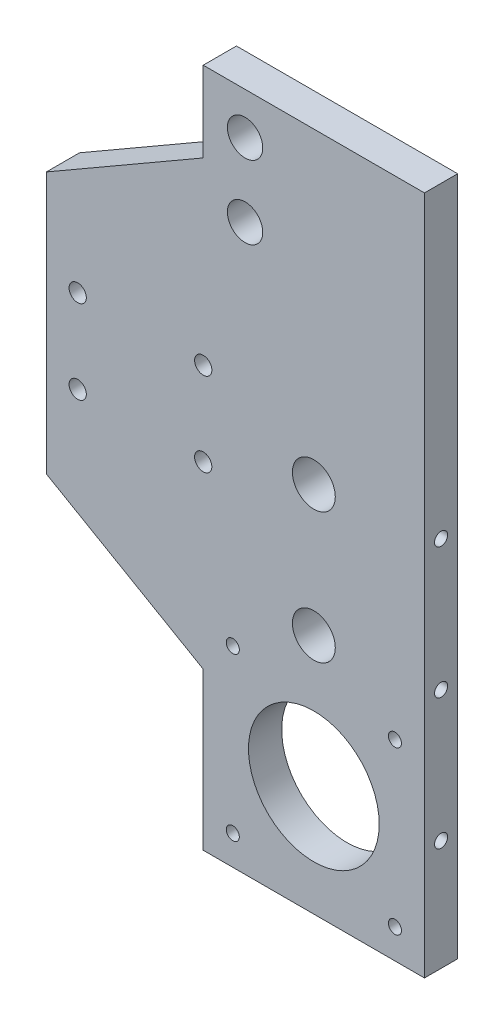
SolidWorks part; units mm, degrees
material "6061 Alloy"
ref_plane "Front Plane" through (0, 0, 0) normal (0, 0, 1) x (1, 0, 0)
ref_plane "Top Plane" through (0, 0, 0) normal (0, 1, 0) x (1, 0, 0)
ref_plane "Right Plane" through (0, 0, 0) normal (1, 0, 0) x (0, 0, -1)
sketch "Sketch2" plane through (0, 0, 0) normal (0, 0, 1) x (1, 0, 0)
  line L0 (0, 0) -> (0, -21.15) construction
  line L1 (-21.15, -21.15) -> (21.15, -21.15)
  line L2 (-21.15, -21.15) -> (-21.15, 108.85)
  line L3 (-21.15, 108.85) -> (21.15, 108.85)
  line L4 (21.15, -21.15) -> (21.15, 108.85)
  circle A0 centre (0, 0) radius 12.5
  circle A1 centre (0, 25) radius 4.1
  circle A2 centre (0, 50) radius 4.1
  dimension "D1" = 25
  dimension "D5" = 25
  dimension "D7" = 8.2
  dimension "D2" = 21.15
  dimension "D3" = 42.3
  dimension "D4" = 130
  dimension "D6" = 25
extrude "Boss-Extrude1" add sketch "Sketch2" along normal blind 6.35
sketch "Sketch3" plane through (21.15, 0, 0) normal (-1, 0, 0) x (0, 0, 1)
  line L0 (6.35, -12.5) -> (6.35, 12.5) construction
  line L1 (6.35, 20.9) -> (6.35, 29.1) construction
  line L2 (6.35, 45.9) -> (6.35, 54.1) construction
  line L3 (6.35, -12.5) -> (6.35, 12.5) construction
  line L4 (6.35, 20.9) -> (6.35, 29.1) construction
  line L5 (6.35, 45.9) -> (6.35, 54.1) construction
  line L6 (3.175, 108.85) -> (3.175, -21.15) construction
  line L7 (6.35, 108.85) -> (0, 108.85) construction
  line L8 (6.35, -21.15) -> (0, -21.15) construction
  line L9 (6.35, 0) -> (3.175, 0) construction
  line L10 (6.35, 25) -> (3.175, 25) construction
  line L11 (6.35, 50) -> (3.175, 50) construction
  point P13 (3.175, 0)
  point P16 (3.175, 25)
  point P18 (3.175, 50)
hole_wizard "Tap Drill for M3x0.5 Tap1" positions "Sketch3" profile "Sketch4" hole size "M3x0.5" standard "ANSI Metric"
sketch "Sketch4" plane through (21.15, 50, 3.175) normal (0, 1, 0) x (0, 0, -1)
  line L0 (0, 0) -> (0, 21.9011)
  line L1 (0, 21.9011) -> (1.25, 21.15)
  line L2 (1.25, 21.15) -> (1.25, 0)
  line L5 (1.25, 0) -> (0, 0)
  line L10 (0, 21.9011) -> (-1.25, 21.15) construction
  line L11 (0, -6.35) -> (0, 107.95) construction
  dimension "Hole Dia." = 2.5
  dimension "Hole Depth" = 21.15
  dimension "Drill Angle" = 118
sketch "Sketch5" plane through (0, 0, 6.35) normal (0, 0, 1) x (1, 0, 0)
  line L1 (-15.5, -15.5) -> (15.5, -15.5) construction
  line L2 (-15.5, -15.5) -> (-15.5, 15.5) construction
  line L3 (-15.5, 15.5) -> (15.5, 15.5) construction
  line L4 (15.5, -15.5) -> (15.5, 15.5) construction
  line L5 (-15.5, -15.5) -> (15.5, 15.5) construction
  line L6 (-15.5, 15.5) -> (15.5, -15.5) construction
  point P0 (0, 0)
  dimension "D1" = 31
hole_wizard "Tap Drill for M3x0.5 Tap2" positions "Sketch7" profile "Sketch9" hole size "M3x0.5" standard "ANSI Metric" end condition through all
sketch "Sketch7" plane through (0, 0, 6.35) normal (0, 0, 1) x (1, 0, 0)
  point P0 (-15.5, 15.5)
  point P3 (-15.5, -15.5)
  point P6 (15.5, -15.5)
  point P9 (15.5, 15.5)
sketch "Sketch9" plane through (-15.5, 15.5, 6.35) normal (1, 0, 0) x (0, -1, 0)
  line L0 (0, 0) -> (0, 6.35)
  line L1 (0, 6.35) -> (1.25, 6.35)
  line L2 (1.25, 6.35) -> (1.25, 0)
  line L5 (1.25, 0) -> (0, 0)
  line L11 (0, -6.35) -> (0, 107.95) construction
  dimension "Thru Hole Dia." = 2.5
  dimension "Thru Hole Depth" = 6.35
sketch "Sketch11" plane through (0, 0, 6.35) normal (0, 0, 1) x (1, 0, 0)
  line L0 (-13.15, 108.85) -> (-13.15, 78.85) construction
  line L1 (21.15, 108.85) -> (-21.15, 108.85) construction
  line L2 (-13.15, 78.85) -> (-21.15, 78.85) construction
  line L3 (-21.15, 108.85) -> (-21.15, -21.15) construction
  point P7 (-13.15, 100.85)
  point P8 (-13.15, 86.85)
  dimension "D1" = 8
  dimension "D2" = 8
  dimension "D3" = 30
  dimension "D4" = 8
hole_wizard "1/4 Clearance Hole1" positions "Sketch11" profile "Sketch12" hole size "1/4" standard "ANSI Inch" end condition through all
sketch "Sketch12" plane through (-13.15, 86.85, 6.35) normal (1, 0, 0) x (0, -1, 0)
  line L0 (0, 0) -> (0, 6.35)
  line L1 (0, 6.35) -> (3.3782, 6.35)
  line L2 (3.3782, 6.35) -> (3.3782, 0)
  line L5 (3.3782, 0) -> (0, 0)
  line L11 (0, -6.35) -> (0, 107.95) construction
  dimension "Thru Hole Dia." = 6.7564
  dimension "Thru Hole Depth" = 6.35
sketch "Sketch13" plane through (0, 0, 6.35) normal (0, 0, 1) x (1, 0, 0)
  line L0 (-21.15, 8.85) -> (-51.15, 26.1705)
  line L2 (-51.15, 26.1705) -> (-51.15, 76.1705)
  line L3 (-51.15, 76.1705) -> (-21.15, 93.491)
  line L4 (-21.15, 93.491) -> (-21.15, 8.85)
  line L6 (-21.15, 108.85) -> (-21.15, -21.15) construction
  dimension "D1" = 60
  dimension "D2" = 60
  dimension "D3" = 30
  dimension "D4" = 50
  dimension "D5" = 30
extrude "Boss-Extrude2" add sketch "Sketch13" against normal up to surface (6.35 mm away) up to face at (-9.7718, 100.85, 0)
sketch "Sketch14" plane through (0, 0, 6.35) normal (0, 0, 1) x (1, 0, 0)
  line L0 (-51.15, 51.1705) -> (-33.15, 51.1705) construction
  line L1 (-51.15, 76.1705) -> (-51.15, 26.1705) construction
  line L3 (-45.15, 43.1705) -> (-21.15, 43.1705) construction
  line L4 (-45.15, 43.1705) -> (-45.15, 59.1705) construction
  line L5 (-45.15, 59.1705) -> (-21.15, 59.1705) construction
  line L6 (-21.15, 43.1705) -> (-21.15, 59.1705) construction
  line L7 (-45.15, 43.1705) -> (-21.15, 59.1705) construction
  line L8 (-45.15, 59.1705) -> (-21.15, 43.1705) construction
  dimension "D1" = 16
  dimension "D2" = 24
  dimension "D3" = 18
hole_wizard "Tap Drill for M4x0.7 Tap1" positions "Sketch15" profile "Sketch16" hole size "M4x0.7" standard "ANSI Metric" end condition through all
sketch "Sketch15" plane through (0, 0, 6.35) normal (0, 0, 1) x (1, 0, 0)
  point P0 (-45.15, 59.1705)
  point P3 (-21.15, 59.1705)
  point P6 (-21.15, 43.1705)
  point P9 (-45.15, 43.1705)
sketch "Sketch16" plane through (-45.15, 59.1705, 6.35) normal (1, 0, 0) x (0, -1, 0)
  line L0 (0, 0) -> (0, 6.35)
  line L1 (0, 6.35) -> (1.65, 6.35)
  line L2 (1.65, 6.35) -> (1.65, 0)
  line L5 (1.65, 0) -> (0, 0)
  line L11 (0, -6.35) -> (0, 107.95) construction
  dimension "Thru Hole Dia." = 3.3
  dimension "Thru Hole Depth" = 6.35
